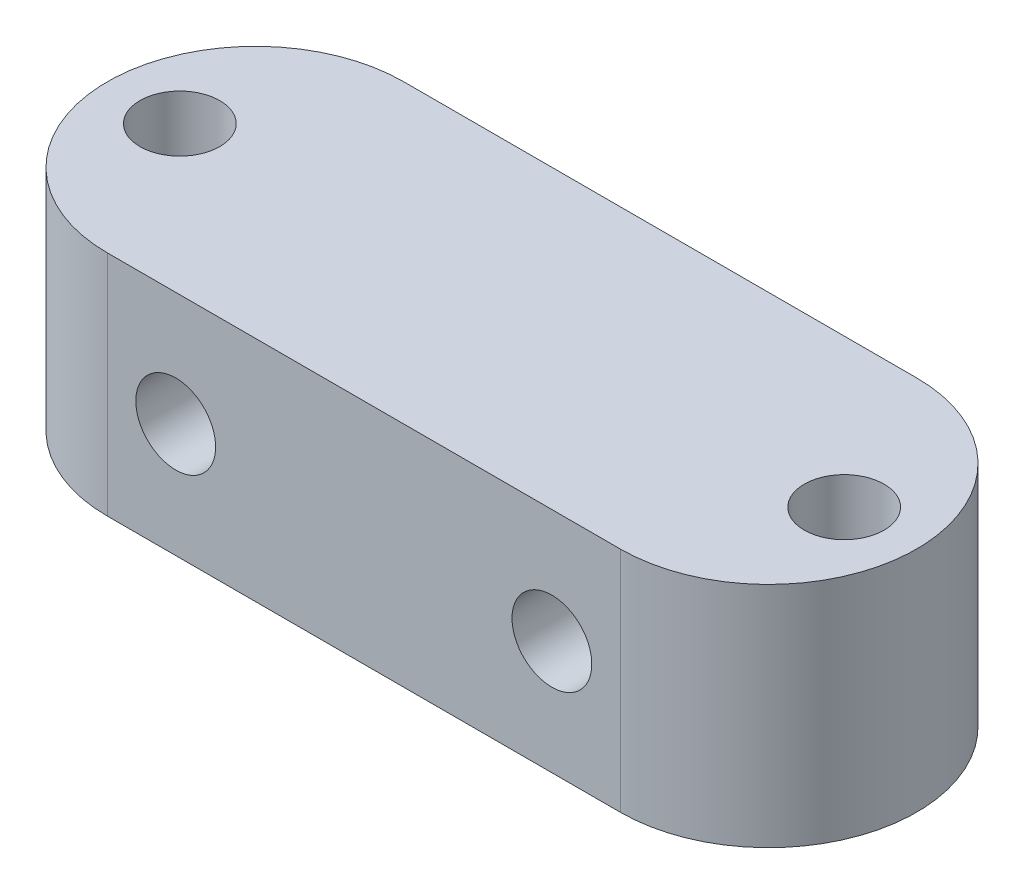
SolidWorks part; units mm, degrees
ref_plane "前视基准面" through (0, 0, 0) normal (0, 0, 1) x (1, 0, 0)
ref_plane "上视基准面" through (0, 0, 0) normal (0, 1, 0) x (1, 0, 0)
ref_plane "右视基准面" through (0, 0, 0) normal (1, 0, 0) x (0, 0, -1)
sketch "草图1" plane through (0, 0, 0) normal (0, 1, 0) x (1, 0, 0)
  line L1 (-102.0993, 5.9483) -> (-79.5993, 5.9483)
  line L3 (-102.0993, -7.0517) -> (-79.5993, -7.0517)
  circle A0 centre (-105.4193, -0.5517) radius 1.75
  circle A1 centre (-76.2793, -0.5517) radius 1.75
  arc A2 (-102.0993, 5.9483) -> (-102.0993, -7.0517) centre (-102.0993, -0.5517) ccw
  arc A3 (-79.5993, -7.0517) -> (-79.5993, 5.9483) centre (-79.5993, -0.5517) ccw
  dimension "D1" = 29.14
  dimension "D2" = 3.5
  dimension "D3" = 3.5
  dimension "D8" = 6.5
  dimension "D11" = 6.5
  dimension "D7" = 6.5
extrude "凸台-拉伸1" add sketch "草图1" along normal blind 10
sketch "草图2" plane through (0, 0, -5.9483) normal (0, 0, -1) x (-1, 0, 0)
  line L0 (79.5993, 0) -> (102.0993, 0) construction
  line L2 (79.5993, 10) -> (79.5993, 0) construction
  line L3 (102.0993, 10) -> (102.0993, 0) construction
  circle A0 centre (99.0993, 5) radius 1.75
  circle A1 centre (82.5993, 5) radius 1.75
  dimension "D1" = 5
  dimension "D5" = 3.5
  dimension "D6" = 3.5
  dimension "D2" = 5
  dimension "D3" = 3
  dimension "D4" = 3
extrude "切除-拉伸1" cut sketch "草图2" against normal blind 21
